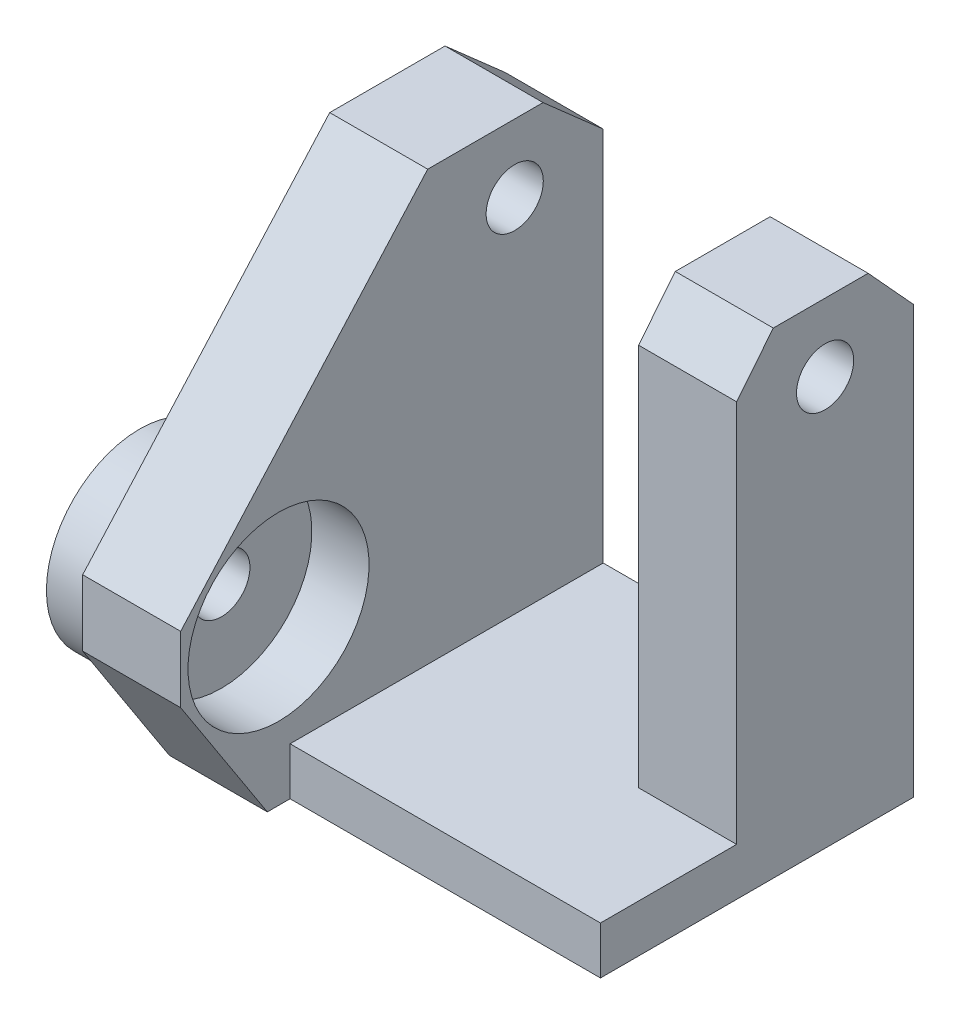
SolidWorks part; units mm, degrees
ref_plane "前视基准面" through (0, 0, 0) normal (0, 0, 1) x (1, 0, 0)
ref_plane "上视基准面" through (0, 0, 0) normal (0, 1, 0) x (1, 0, 0)
ref_plane "右视基准面" through (0, 0, 0) normal (1, 0, 0) x (0, 0, -1)
sketch "草图4" plane through (0, 0, 0) normal (0, 0, 1) x (1, 0, 0)
  line L0 (0, 6.0493) -> (0, -6.8282) construction
  line L1 (15, 0) -> (-15, 0)
  line L2 (-15, 0) -> (-15, 35)
  line L3 (-15, 35) -> (-7.8, 35)
  line L4 (-7.8, 35) -> (-7.8, 3.5)
  line L5 (-7.8, 3.5) -> (7.8, 3.5)
  line L6 (7.8, 35) -> (7.8, 3.5)
  line L7 (15, 35) -> (7.8, 35)
  line L8 (15, 0) -> (15, 35)
  point P10 (0, 3.5)
  point P13 (0, 0)
  dimension "D1" = 15.6
  dimension "D2" = 35
  dimension "D3" = 3.5
  dimension "D4" = 30
extrude "凸台-拉伸3" add sketch "草图4" along normal blind 13
sketch "草图5" plane through (15, 0, 0) normal (1, 0, 0) x (0, 0, -1)
  line L0 (-6.5, 35) -> (-6.5, 6.3551) construction
  line L1 (-13, 35) -> (0, 35) construction
  circle A0 centre (-6.5, 30) radius 2.1
  dimension "D1" = 4.2
  dimension "D2" = 5
extrude "切除-拉伸2" cut sketch "草图5" against normal through all
sketch "草图6" plane through (0, 0, 13) normal (0, 0, 1) x (1, 0, 0)
  line L1 (-15, 35) -> (-7.8, 35)
  line L2 (-15, 35) -> (-15, 0)
  line L3 (-15, 0) -> (-7.8, 0)
  line L4 (-7.8, 35) -> (-7.8, 0)
  line L6 (-15, 0) -> (15, 0) construction
  line L7 (-7.8, 3.5) -> (-7.8, 35) construction
extrude "凸台-拉伸4" add sketch "草图6" along normal blind 20
sketch "草图7" plane through (-15, 0, 0) normal (-1, 0, 0) x (0, 0, 1)
  circle A0 centre (23.8494, 12) radius 2.1
  circle A1 centre (6.5, 30) radius 2.1 construction
  dimension "D1" = 4.2
  dimension "D2" = 25
  dimension "D3" = 18
extrude "切除-拉伸3" cut sketch "草图7" against normal blind 20
sketch "草图8" plane through (0, 0, 13) normal (0, 0, 1) x (1, 0, 0)
  line L1 (-7.8, 3.5) -> (15, 3.5)
  line L2 (-7.8, 3.5) -> (-7.8, 0)
  line L3 (-7.8, 0) -> (15, 0)
  line L4 (15, 3.5) -> (15, 0)
extrude "凸台-拉伸5" add sketch "草图8" along normal blind 10
sketch "草图9" plane through (-7.8, 0, 0) normal (1, 0, 0) x (0, 0, -1)
  circle A0 centre (-23.8494, 12) radius 6.65
  dimension "D1" = 13.3
extrude "切除-拉伸4" cut sketch "草图9" against normal blind 4.2
sketch "草图10" plane through (-15, 0, 0) normal (-1, 0, 0) x (0, 0, 1)
  line L0 (12.8908, 35) -> (31.0362, 14.6717)
  line L1 (33, 35) -> (0, 35) construction
  line L2 (33, 35) -> (33, 0) construction
  line L4 (33, 35) -> (12.8908, 35)
  line L5 (31.0362, 9.8143) -> (24.6701, 0)
  line L6 (33, 0) -> (0, 0) construction
  line L7 (24.6701, 0) -> (33, 0)
  line L8 (33, 0) -> (33, 10.1342)
  line L9 (0, 35) -> (0, 31.1079)
  line L10 (0, 35) -> (0, 0) construction
  line L11 (0, 31.1079) -> (4.4193, 35)
  line L12 (4.4193, 35) -> (0, 35)
  line L13 (31.0362, 14.6717) -> (31.0362, 9.8143)
  line L14 (33, 35) -> (33, 10.1342)
extrude "切除-拉伸5" cut sketch "草图10" against normal blind 10
sketch "草图11" plane through (15, 0, 0) normal (1, 0, 0) x (0, 0, -1)
  line L0 (-3.3368, 35) -> (0, 31.3482)
  line L1 (-13, 35) -> (0, 35) construction
  line L2 (0, 0) -> (0, 35) construction
  line L3 (0, 31.3482) -> (0, 35)
  line L4 (0, 35) -> (-3.3368, 35)
  line L5 (-10.3038, 35) -> (-13, 35)
  line L6 (-13, 35) -> (-13, 31.6571)
  line L7 (-13, 3.5) -> (-13, 35) construction
  line L8 (-13, 31.6571) -> (-10.3038, 35)
extrude "切除-拉伸6" cut sketch "草图11" against normal blind 10
sketch "草图12" plane through (0, 3.5, 0) normal (0, 1, 0) x (1, 0, 0)
  line L3 (7.8, 0) -> (-7.8, 0) construction
  line L4 (15, -23) -> (15, -13) construction
  circle A0 centre (-4.5, -5) radius 1.65
  circle A1 centre (-4.5, -17) radius 1.65
  circle A2 centre (9.5, -17) radius 1.65
  dimension "D1" = 3.3
  dimension "D4" = 14
  dimension "D5" = 12
  dimension "D3" = 5
  dimension "D2" = 5.5
sketch "草图14" plane through (-15, 0, 0) normal (-1, 0, 0) x (0, 0, 1)
  circle A0 centre (23.8494, 12) radius 5.65
  circle A1 centre (23.8494, 12) radius 6.85
  dimension "D1" = 1.2
  dimension "D2" = 11.3
extrude "凸台-拉伸7" add sketch "草图14" along normal blind 3
